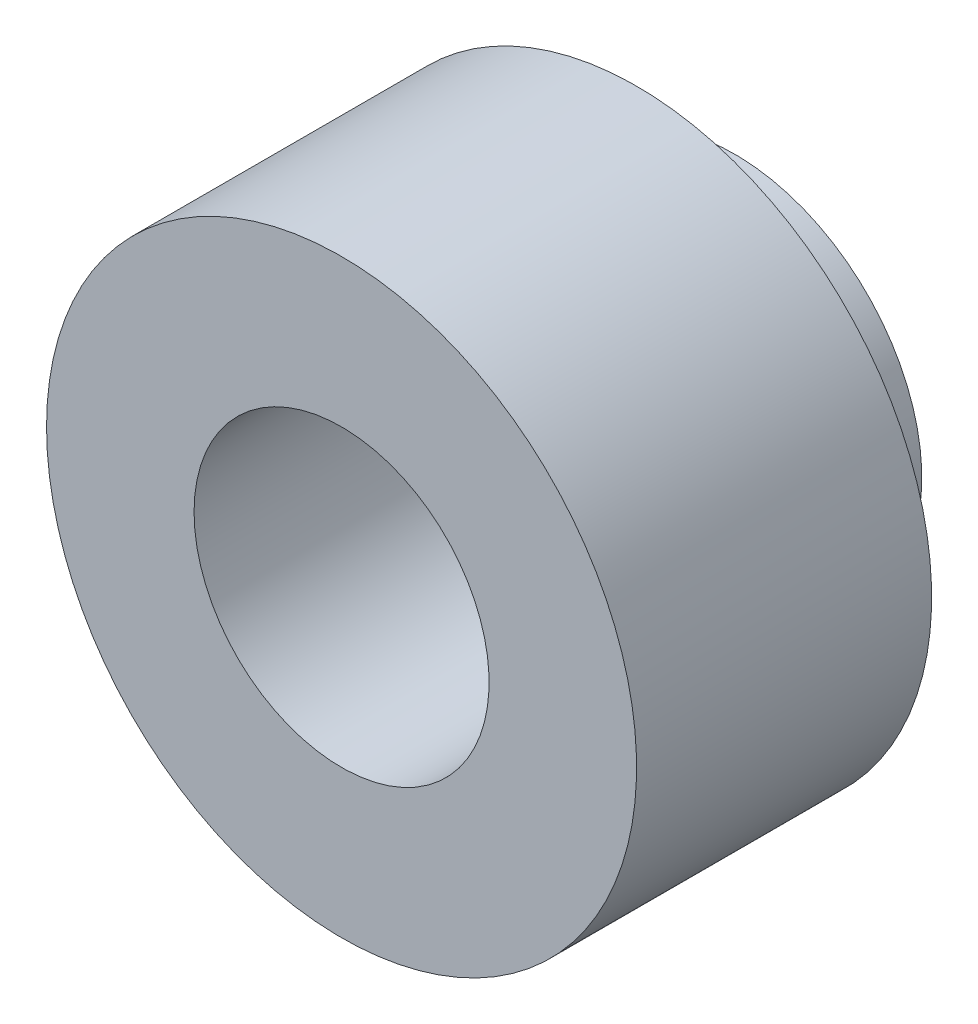
SolidWorks part; units mm, degrees
ref_plane "Front Plane" through (0, 0, 0) normal (0, 0, 1) x (1, 0, 0)
ref_plane "Top Plane" through (0, 0, 0) normal (0, 1, 0) x (1, 0, 0)
ref_plane "Right Plane" through (0, 0, 0) normal (1, 0, 0) x (0, 0, -1)
sketch "Sketch1" plane through (0, 0, 0) normal (0, 1, 0) x (1, 0, 0)
  line L0 (0, 567.3249) -> (0, -736.329) construction
  line L1 (-187.5, 0) -> (-375, 0)
  line L2 (-375, 0) -> (-375, 375)
  line L3 (-375, 375) -> (-237.5, 375)
  line L4 (-237.5, 375) -> (-237.5, 500)
  line L5 (-237.5, 500) -> (-187.5, 500)
  line L6 (-187.5, 500) -> (-187.5, 0)
  dimension "D1" = 375
revolve "Revolve1" add sketch "Sketch1" angle 360 about L0
